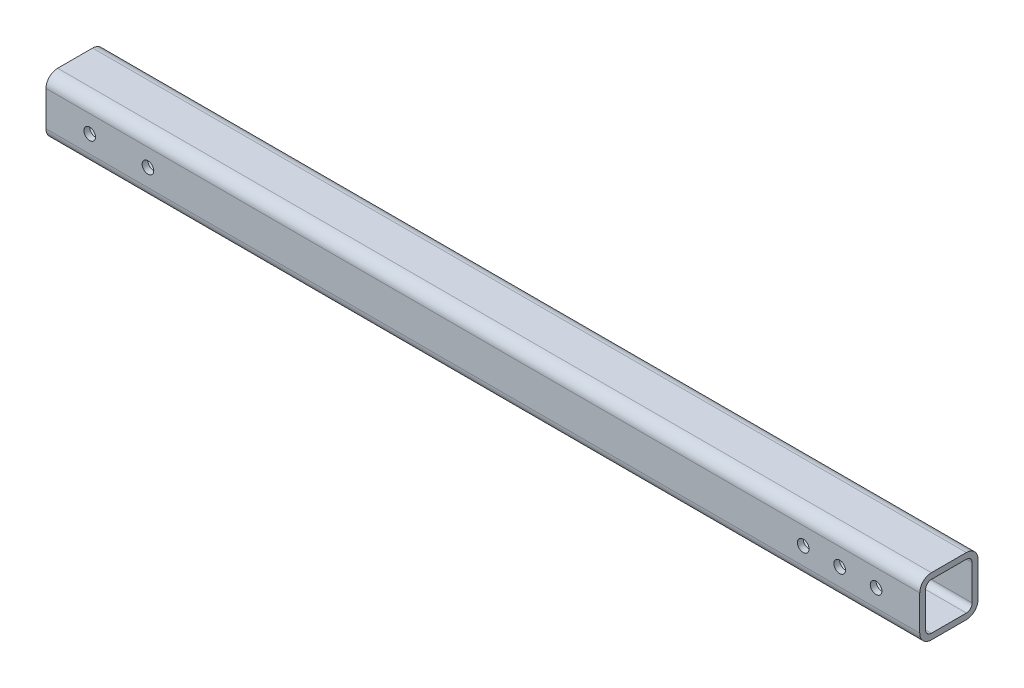
SolidWorks part; units mm, degrees
ref_plane "Alzado" through (0, 0, 0) normal (0, 0, 1) x (1, 0, 0)
ref_plane "Planta" through (0, 0, 0) normal (0, 1, 0) x (1, 0, 0)
ref_plane "Vista lateral" through (0, 0, 0) normal (1, 0, 0) x (0, 0, -1)
sketch "Croquis1" plane through (0, 0, 0) normal (0, 1, 0) x (1, 0, 0)
  line L0 (-300, 0) -> (300, 0)
  point P4 (0, 0)
  dimension "D1" = 600
other "Tubo cuadrado 40 X 40 X 4(1)"
ref_plane "Plano1" through (-300, 0, 0) normal (1, 0, 0) x (0, 0, -1)
sketch "Sketch1" plane through (-300, 0, 0) normal (1, 0, 0) x (0, 0, -1)
  line L0 (-12, -16) -> (12, -16)
  line L1 (-16, -12) -> (-16, 12)
  line L2 (12, 16) -> (-12, 16)
  line L3 (16, 12) -> (16, -12)
  line L4 (-12, -20) -> (12, -20)
  line L5 (-20, -12) -> (-20, 12)
  line L6 (12, 20) -> (-12, 20)
  line L7 (20, 12) -> (20, -12)
  arc A0 (20, 12) -> (12, 20) centre (12, 12) ccw
  arc A1 (12, -20) -> (20, -12) centre (12, -12) ccw
  arc A2 (-20, -12) -> (-12, -20) centre (-12, -12) ccw
  arc A3 (-12, 20) -> (-20, 12) centre (-12, 12) ccw
  arc A4 (-12, 16) -> (-16, 12) centre (-12, 12) ccw
  arc A5 (16, 12) -> (12, 16) centre (12, 12) ccw
  arc A6 (12, -16) -> (16, -12) centre (12, -12) ccw
  arc A7 (-16, -12) -> (-12, -16) centre (-12, -12) ccw
  point P0 (-20, 0)
  point P1 (20, 0)
  point P2 (0, 20)
  point P3 (0, -20)
  point P4 (0, 0)
  point P5 (-20, -20)
  point P6 (20, -20)
  point P7 (20, 20)
  point P8 (-20, 20)
  point P33 (0, 0)
  dimension "D1" = 8
  dimension "Thickness" = 4
  dimension "V_leg" = 40
sketch "Croquis3" plane through (0, 0, 0) normal (0, 0, 1) x (1, 0, 0)
  line L0 (300, 0) -> (270, 0) construction
  line L1 (300, 12) -> (300, -12) construction
  line L2 (-300, 0) -> (300, 0) construction
  line L3 (270, 0) -> (245, 0) construction
  line L4 (245, 0) -> (220, 0) construction
  line L5 (-300, 0) -> (-270, 0) construction
  line L6 (-270, 0) -> (-230, 0) construction
  circle A0 centre (-270, 0) radius 4
  circle A1 centre (-230, 0) radius 4
  circle A2 centre (220, 0) radius 4
  circle A3 centre (245, 0) radius 4
  circle A4 centre (270, 0) radius 4
  dimension "D1" = 8
  dimension "D2" = 8
  dimension "D3" = 8
  dimension "D4" = 8
  dimension "D5" = 8
  dimension "D6" = 30
  dimension "D7" = 40
  dimension "D8" = 25
  dimension "D9" = 25
  dimension "D10" = 30
extrude "Cortar-Extruir1" cut sketch "Croquis3" against normal mid plane 50 contours A0 | A1 | A2 | A3 | A4
